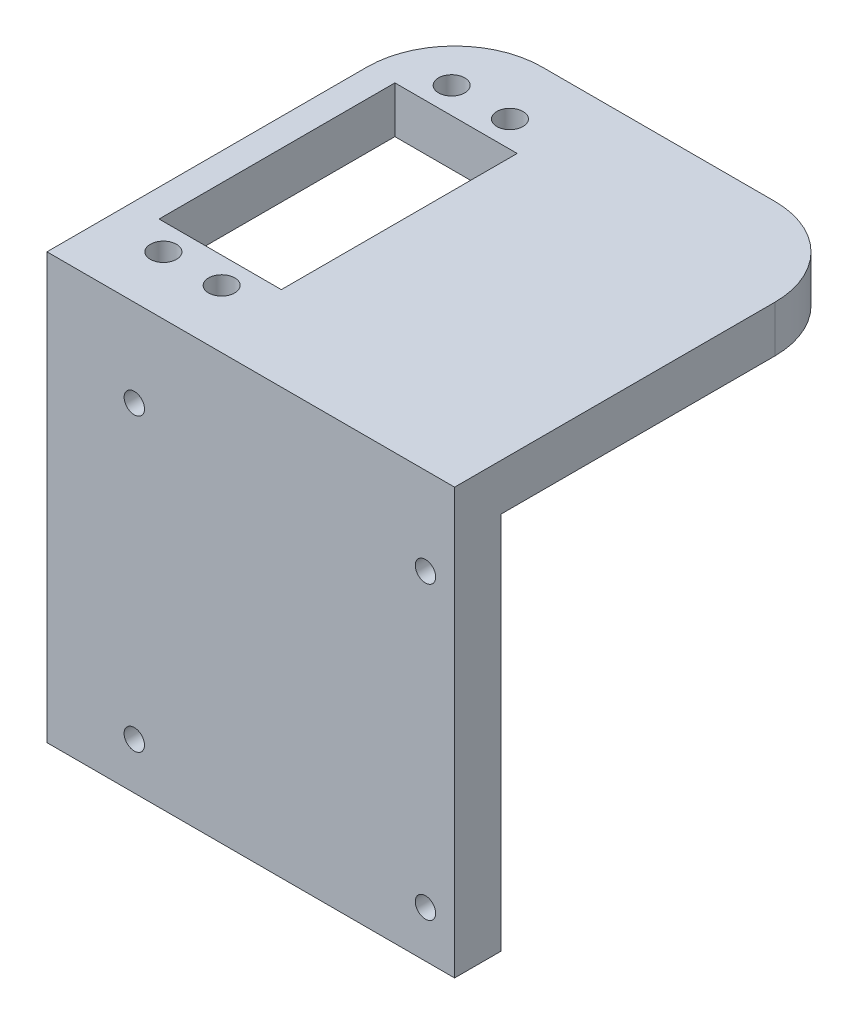
SolidWorks part; units mm, degrees
ref_plane "Front Plane" through (0, 0, 0) normal (0, 0, 1) x (1, 0, 0)
ref_plane "Top Plane" through (0, 0, 0) normal (0, 1, 0) x (1, 0, 0)
ref_plane "Right Plane" through (0, 0, 0) normal (1, 0, 0) x (0, 0, -1)
sketch "Sketch2" plane through (0, 0, 0) normal (0, 1, 0) x (1, 0, 0)
  line L1 (-15, 37.5) -> (55, 37.5)
  line L2 (-15, 37.5) -> (-15, -32.5)
  line L3 (-15, -32.5) -> (55, -32.5)
  line L4 (55, 37.5) -> (55, -32.5)
  dimension "D1" = 70
  dimension "D2" = 70
  dimension "D3" = 55
  dimension "D4" = 37.5
extrude "Boss-Extrude1" add sketch "Sketch2" along normal blind 8
sketch "Sketch4" plane through (0, 0, 0) normal (0, -1, 0) x (-1, 0, 0)
  line L0 (-55, -32.5) -> (-55, 37.5) construction
  line L1 (15, -32.5) -> (-55, -32.5)
  line L2 (15, -32.5) -> (15, -24.5)
  line L3 (15, -24.5) -> (-55, -24.5)
  line L4 (-55, -32.5) -> (-55, -24.5)
  dimension "D1" = 8
extrude "Boss-Extrude2" add sketch "Sketch4" along normal blind 65
sketch "Sketch6" plane through (0, 0, 24.5) normal (0, 0, -1) x (-1, 0, 0)
  line L0 (15, 0) -> (-55, 0) construction
  line L1 (-55, -65) -> (-55, 0) construction
  circle A0 centre (-50, -7) radius 1.75
  circle A1 centre (0, -7) radius 1.75
  circle A2 centre (-50, -57) radius 1.75
  circle A3 centre (0, -57) radius 1.75
  dimension "D1" = 3.5
  dimension "D2" = 3.5
  dimension "D3" = 3.5
  dimension "D4" = 3.5
  dimension "D5" = 7
  dimension "D6" = 7
  dimension "D7" = 50
  dimension "D8" = 50
  dimension "D9" = 50
  dimension "D10" = 5
  dimension "D11" = 5
extrude "Cut-Extrude1" cut sketch "Sketch6" against normal blind 10
sketch "Sketch7" plane through (0, 0, 24.5) normal (0, 0, -1) x (-1, 0, 0)
  circle A0 centre (-50, -7) radius 3.5
  circle A1 centre (0, -7) radius 3.5
  circle A2 centre (0, -57) radius 3.5
  circle A3 centre (-50, -57) radius 3.5
  dimension "D1" = 7
  dimension "D2" = 7
  dimension "D3" = 7
  dimension "D4" = 7
extrude "Cut-Extrude2" cut sketch "Sketch7" against normal blind 3
sketch "Sketch9" plane through (0, 8, 0) normal (0, 1, 0) x (1, 0, 0)
  line L0 (-15, -32.5) -> (55, -32.5) construction
  line L1 (-10.25, 22.5) -> (10.75, 22.5)
  line L2 (-10.25, 22.5) -> (-10.25, -18)
  line L3 (-10.25, -18) -> (10.75, -18)
  line L4 (10.75, 22.5) -> (10.75, -18)
  dimension "D1" = 21
  dimension "D2" = 40.5
  dimension "D3" = 10.25
  dimension "D4" = 55
extrude "Cut-Extrude3" cut sketch "Sketch9" against normal blind 10
sketch "Sketch10" plane through (0, 8, 0) normal (0, 1, 0) x (1, 0, 0)
  line L0 (10.75, 22.5) -> (-10.25, 22.5) construction
  circle A0 centre (-5, 27) radius 2.25
  circle A1 centre (5, 27) radius 2.25
  circle A2 centre (-5, -22.5) radius 2.25
  circle A3 centre (5, -22.5) radius 2.25
  dimension "D1" = 4.5
  dimension "D2" = 4.5
  dimension "D3" = 4.5
  dimension "D4" = 4.5
  dimension "D5" = 5
  dimension "D6" = 5
  dimension "D7" = 5
  dimension "D8" = 5
  dimension "D9" = 49.5
  dimension "D10" = 49.5
  dimension "D11" = 4.5
  dimension "D12" = 4.5
extrude "Cut-Extrude4" cut sketch "Sketch10" against normal blind 10
fillet "Fillet1" radius 15 1 edges at (55, 4, -37.5)
fillet "Fillet2" radius 15 1 edges at (-15, 4, -37.5)
